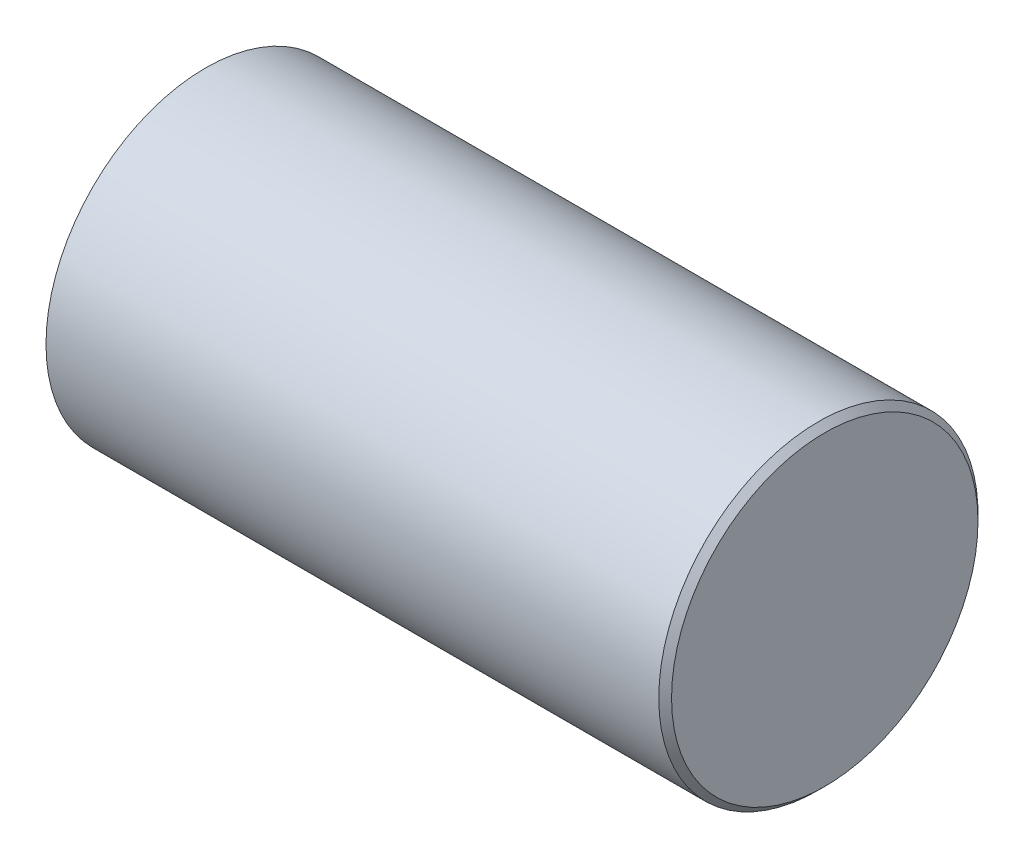
SolidWorks part; units mm, degrees
ref_plane "Front Plane" through (0, 0, 0) normal (0, 0, 1) x (1, 0, 0)
ref_plane "Top Plane" through (0, 0, 0) normal (0, 1, 0) x (1, 0, 0)
ref_plane "Right Plane" through (0, 0, 0) normal (1, 0, 0) x (0, 0, -1)
sketch "Sketch1" plane through (0, 0, 0) normal (0, 0, 1) x (1, 0, 0)
  line L1 (0, 0) -> (100, 0)
  line L2 (0, 0) -> (0, 25)
  line L3 (0, 25) -> (100, 25)
  line L4 (100, 0) -> (100, 25)
  arc A0 (3.0196, 25) -> (0, 0) centre (105, 0) ccw
  dimension "D1" = 210
  dimension "D2" = 25
  dimension "D3" = 100
revolve "Revolve1" add sketch "Sketch1" angle 360 about L1
chamfer "Chamfer1" distance 1 angle 45 1 edges at (100, 0, 25)
